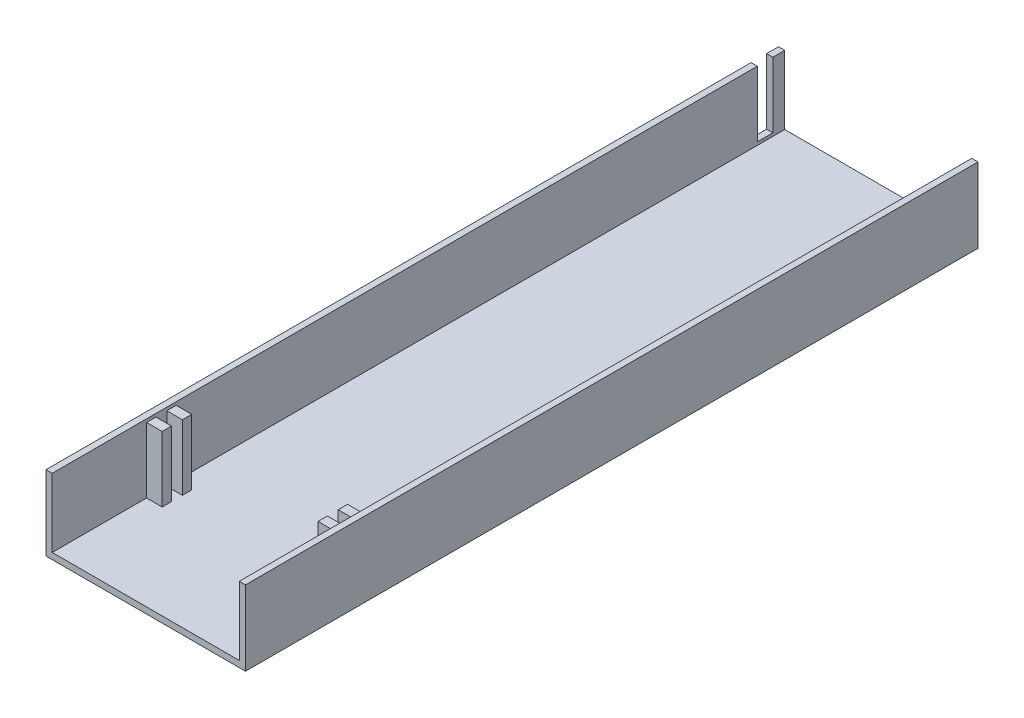
SolidWorks part; units mm, degrees
ref_plane "Front Plane" through (0, 0, 0) normal (0, 0, 1) x (1, 0, 0)
ref_plane "Top Plane" through (0, 0, 0) normal (0, 1, 0) x (1, 0, 0)
ref_plane "Right Plane" through (0, 0, 0) normal (1, 0, 0) x (0, 0, -1)
sketch "Sketch1" plane through (0, 0, 0) normal (0, 0, 1) x (1, 0, 0)
  line L0 (-30, 12) -> (-30, 10)
  line L1 (30, -10) -> (-30, -10)
  line L2 (30, -10) -> (30, 10)
  line L3 (30, 10) -> (-30, 10) construction
  line L4 (-30, -10) -> (-30, 10)
  line L5 (30, -10) -> (-30, 10) construction
  line L6 (30, 10) -> (-30, -10) construction
  line L7 (30, 10) -> (30, 12)
  line L8 (32, -12) -> (32, 12)
  line L9 (32, 12) -> (30, 12)
  line L10 (-32, -12) -> (-32, 12)
  line L11 (32, -12) -> (-32, -12)
  line L12 (30, 12) -> (-30, 12) construction
  line L13 (-30, 12) -> (-32, 12)
  line L14 (32, 12) -> (-32, 12) construction
  point P0 (0, 0)
  dimension "D1" = 64
  dimension "D2" = 24
  dimension "D3" = 2
extrude "Boss-Extrude1" add sketch "Sketch1" against normal blind 45 and the other way blind 35
sketch "Sketch3" plane through (0, 0, -45) normal (0, 0, -1) x (-1, 0, 0)
  line L0 (-30, -10) -> (-30, 12)
  line L1 (-32, 12) -> (-30, 12) construction
  line L2 (-30, 12) -> (-32, 12)
  line L3 (-32, 12) -> (-32, -12)
  line L4 (-32, -12) -> (32, -12)
  line L5 (32, -12) -> (32, 12)
  line L6 (32, 12) -> (30, 12)
  line L7 (30, 12) -> (30, -10)
  line L8 (30, -10) -> (-30, -10)
extrude "Boss-Extrude3" add sketch "Sketch3" along normal blind 155
sketch "Sketch4" plane through (0, 0, 0) normal (0, 0, 1) x (1, 0, 0)
  line L0 (-29, 8) -> (-29, -10) construction
  line L1 (30, -10) -> (-30, -10) construction
  line L2 (30, -10) -> (30, 10) construction
  line L3 (30, 10) -> (-30, 10) construction
  line L4 (-30, -10) -> (-30, 10) construction
  line L5 (30, -10) -> (-30, 10) construction
  line L6 (30, 10) -> (-30, -10) construction
  line L7 (30, -11) -> (-30, -11)
  line L8 (30, -11) -> (30, 11)
  line L9 (30, 11) -> (-30, 11)
  line L10 (-30, -11) -> (-30, 11)
  line L11 (30, -11) -> (-30, 11) construction
  line L12 (30, 11) -> (-30, -11) construction
  line L13 (-29, -10) -> (29, -10) construction
  point P0 (0, 0)
  point P5 (0, 0)
  dimension "D1" = 1
  dimension "D2" = 1
  dimension "D3" = 1
extrude "Boss-Extrude4" [suppressed] add sketch "Sketch4" along normal mid plane 2
sketch "Sketch5" plane through (0, -10, 0) normal (0, 1, 0) x (1, 0, 0)
  line L0 (-30, -35) -> (-30, 200) construction
  line L1 (30, -1.75) -> (-30, -1.75) construction
  line L2 (30, -1.75) -> (30, 1.75) construction
  line L3 (30, 1.75) -> (-30, 1.75) construction
  line L4 (-30, -1.75) -> (-30, 1.75) construction
  line L5 (30, -1.75) -> (-30, 1.75) construction
  line L6 (30, 1.75) -> (-30, -1.75) construction
  line L7 (-30, -1.75) -> (-25, -1.75)
  line L8 (-25, -1.75) -> (-25, -4.75)
  line L9 (-25, -4.75) -> (-30, -4.75)
  line L10 (-30, -35) -> (-30, 200) construction
  line L11 (-30, -4.75) -> (-30, -1.75)
  line L12 (0, 0) -> (-35.0204, 0) construction
  line L13 (0, 0) -> (0, -11.9502) construction
  line L14 (-30, 4.75) -> (-30, 1.75)
  line L15 (-25, 4.75) -> (-30, 4.75)
  line L16 (-25, 1.75) -> (-25, 4.75)
  line L17 (-30, 1.75) -> (-25, 1.75)
  line L18 (30, -4.75) -> (30, -1.75)
  line L19 (25, -4.75) -> (30, -4.75)
  line L20 (25, -1.75) -> (25, -4.75)
  line L21 (30, -1.75) -> (25, -1.75)
  line L22 (25, 4.75) -> (30, 4.75)
  line L23 (25, 1.75) -> (25, 4.75)
  line L24 (30, 1.75) -> (25, 1.75)
  line L25 (30, 4.75) -> (30, 1.75)
  point P0 (0, 0)
  dimension "D1" = 3.5
  dimension "D2" = 3
  dimension "D3" = 5
extrude "Boss-Extrude5" add sketch "Sketch5" along normal blind 21
sketch "Sketch6" plane through (-32, 0, 0) normal (-1, 0, 0) x (0, 0, 1)
  line L0 (-200, 0) -> (-186.9685, 0) construction
  line L1 (-196.2, 9) -> (-191.2, 9) construction
  line L2 (-196.2, 9) -> (-196.2, -9)
  line L3 (-196.2, -9) -> (-191.2, -9)
  line L4 (-191.2, 9) -> (-191.2, -9)
  line L5 (-200, -12) -> (-200, 12) construction
  line L6 (-196.2, 9) -> (-196.2, 12)
  line L7 (35, 12) -> (-200, 12) construction
  line L8 (-196.2, 12) -> (-191.2, 12)
  line L9 (-191.2, 12) -> (-191.2, 9)
  point P9 (-196.2, 0)
  dimension "D1" = 18
  dimension "D2" = 5
  dimension "D3" = 3.8
extrude "Cut-Extrude1" cut sketch "Sketch6" against normal blind 10
